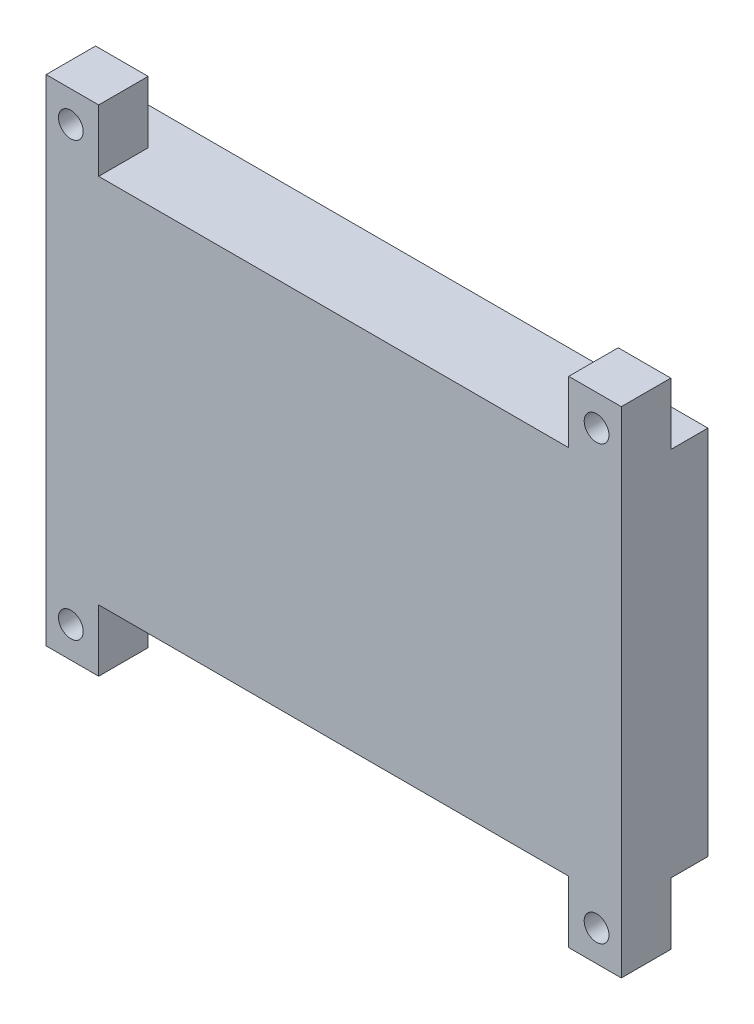
SolidWorks part; units mm, degrees
ref_plane "前视基准面" through (0, 0, 0) normal (0, 0, 1) x (1, 0, 0)
ref_plane "上视基准面" through (0, 0, 0) normal (0, 1, 0) x (1, 0, 0)
ref_plane "右视基准面" through (0, 0, 0) normal (1, 0, 0) x (0, 0, -1)
sketch "草图3" plane through (0, 0, 0) normal (0, 0, 1) x (1, 0, 0)
  line L1 (-46.5, 30) -> (46.5, 30)
  line L2 (-46.5, 30) -> (-46.5, -30)
  line L3 (-46.5, -30) -> (46.5, -30)
  line L4 (46.5, 30) -> (46.5, -30)
  line L5 (-46.5, 30) -> (46.5, -30) construction
  line L6 (-46.5, -30) -> (46.5, 30) construction
  point P0 (0, 0)
  dimension "D1" = 93
  dimension "D2" = 60
extrude "凸台-拉伸1" add sketch "草图3" along normal blind 6
sketch "草图6" plane through (0, 0, 6) normal (0, 0, 1) x (1, 0, 0)
  line L0 (46.5, 30) -> (-46.5, 30) construction
  line L1 (-46.5, 40) -> (46.5, 40)
  line L2 (-46.5, 40) -> (-46.5, -40)
  line L3 (-46.5, -40) -> (46.5, -40)
  line L4 (46.5, 40) -> (46.5, -40)
  line L5 (-46.5, -30) -> (46.5, -30) construction
  dimension "D1" = 10
  dimension "D2" = 10
extrude "凸台-拉伸3" add sketch "草图6" along normal blind 8
sketch "草图7" plane through (0, 0, 6) normal (0, 0, -1) x (-1, 0, 0)
  line L0 (-46.5, 40) -> (46.5, 40) construction
  line L1 (38, 40) -> (-38, 40)
  line L2 (38, 40) -> (38, 30)
  line L3 (38, 30) -> (-38, 30)
  line L4 (-38, 40) -> (-38, 30)
  line L5 (-46.5, 30) -> (46.5, 30) construction
  line L6 (46.5, 40) -> (46.5, 30) construction
  line L7 (-46.5, 30) -> (-46.5, 40) construction
  line L8 (46.5, -30) -> (-46.5, -30) construction
  line L9 (-38, -30) -> (38, -30)
  line L10 (-38, -30) -> (-38, -40)
  line L11 (-38, -40) -> (38, -40)
  line L12 (38, -30) -> (38, -40)
  line L13 (46.5, -40) -> (-46.5, -40) construction
  point P12 (-46.5, 35)
  dimension "D1" = 8.5
  dimension "D2" = 8.5
extrude "切除-拉伸1" cut sketch "草图7" against normal blind 8
sketch "草图8" plane through (0, 0, 6) normal (0, 0, -1) x (-1, 0, 0)
  line L0 (-46.5, 40) -> (-38, 40) construction
  line L1 (0, 7.7) -> (0, -7.7) construction
  line L2 (-46.5, 30) -> (-46.5, 40) construction
  line L3 (7.7, 0) -> (-7.7, 0) construction
  circle A0 centre (-42.5, 35) radius 2
  circle A1 centre (42.5, 35) radius 2
  circle A2 centre (42.5, -35) radius 2
  circle A3 centre (-42.5, -35) radius 2
  point P6 (-46.5, 35.6301)
  point P7 (0, 0)
  dimension "D3" = 4
  dimension "D1" = 5
  dimension "D2" = 4
extrude "切除-拉伸2" cut sketch "草图8" against normal blind 8
